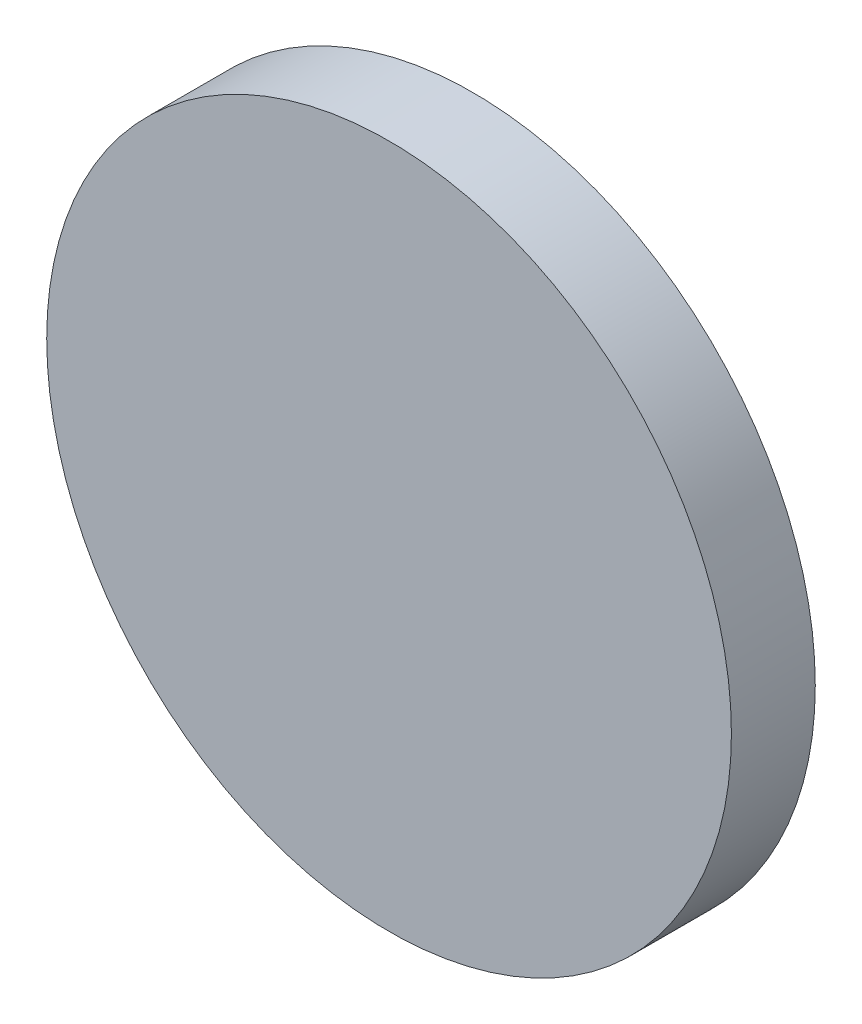
SolidWorks part; units mm, degrees
ref_plane "Front Plane" through (0, 0, 0) normal (0, 0, 1) x (1, 0, 0)
ref_plane "Top Plane" through (0, 0, 0) normal (0, 1, 0) x (1, 0, 0)
ref_plane "Right Plane" through (0, 0, 0) normal (1, 0, 0) x (0, 0, -1)
sketch "Sketch1" plane through (0, 0, 0) normal (0, 0, 1) x (1, 0, 0)
  circle A0 centre (0, 0) radius 40.815
extrude "Boss-Extrude1" add sketch "Sketch1" along normal blind 10
